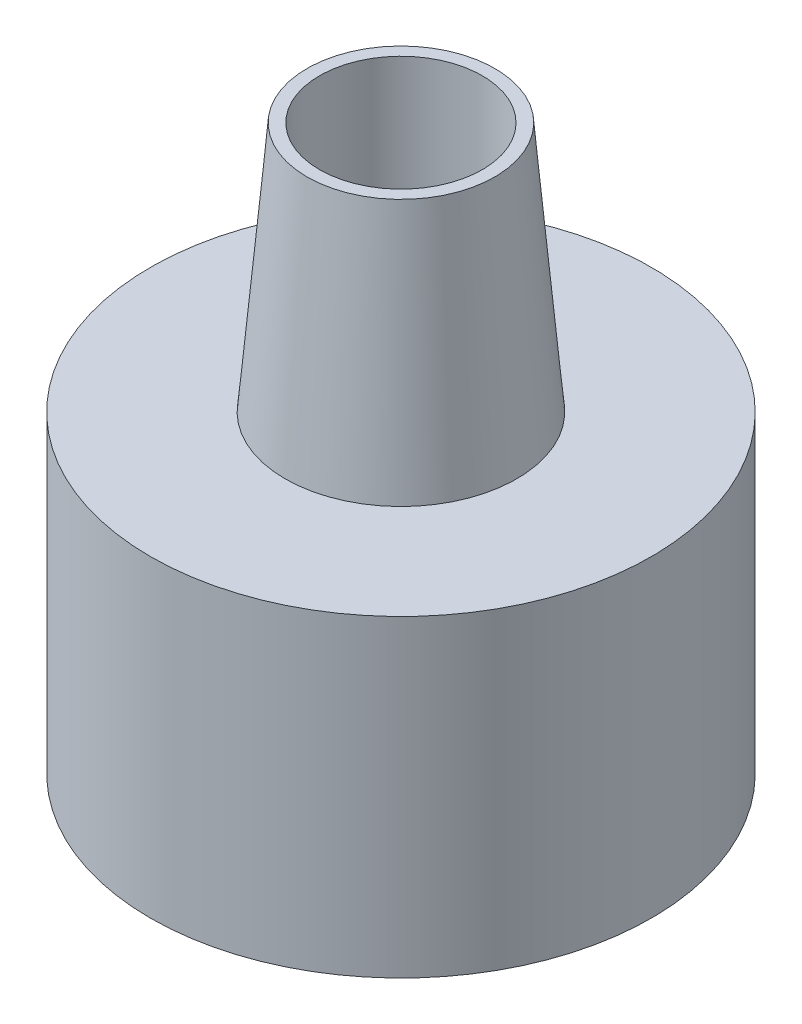
SolidWorks part; units mm, degrees
ref_plane "Front Plane" through (0, 0, 0) normal (0, 0, 1) x (1, 0, 0)
ref_plane "Top Plane" through (0, 0, 0) normal (0, 1, 0) x (1, 0, 0)
ref_plane "Right Plane" through (0, 0, 0) normal (1, 0, 0) x (0, 0, -1)
sketch "Sketch1" plane through (0, 0, 0) normal (1, 0, 0) x (0, 0, -1)
  line L0 (0, 15.0909) -> (0, -14.5909) construction
  line L1 (-6, 3.75) -> (-6, -4.25)
  line L2 (-8, -6.25) -> (-10, -6.25)
  line L3 (-10, -6.25) -> (-10, 6.25)
  line L4 (-10, 6.25) -> (-4.6249, 6.25)
  line L5 (-6, 3.75) -> (-3.25, 3.75)
  line L7 (-3.75, 6.25) -> (-3.75, 16.25) construction
  line L8 (-3.75, 16.25) -> (-3.25, 16.25)
  line L9 (-3.25, 3.75) -> (-3.25, 16.25)
  line L10 (-3.75, 16.25) -> (-4.6249, 6.25)
  line L11 (-4.6249, 6.25) -> (-3.75, 6.25) construction
  line L12 (-6, -4.25) -> (-8, -6.25)
  point P4 (-6, -6.25)
  point P5 (-10, 0)
  dimension "D1" = 12
  dimension "D2" = 20
  dimension "D3" = 12.5
  dimension "D4" = 10
  dimension "D5" = 6.5
  dimension "D6" = 10
  dimension "D7" = 3.75
  dimension "D8" = 95
revolve "Revolve1" add sketch "Sketch1" angle 360 about L0
